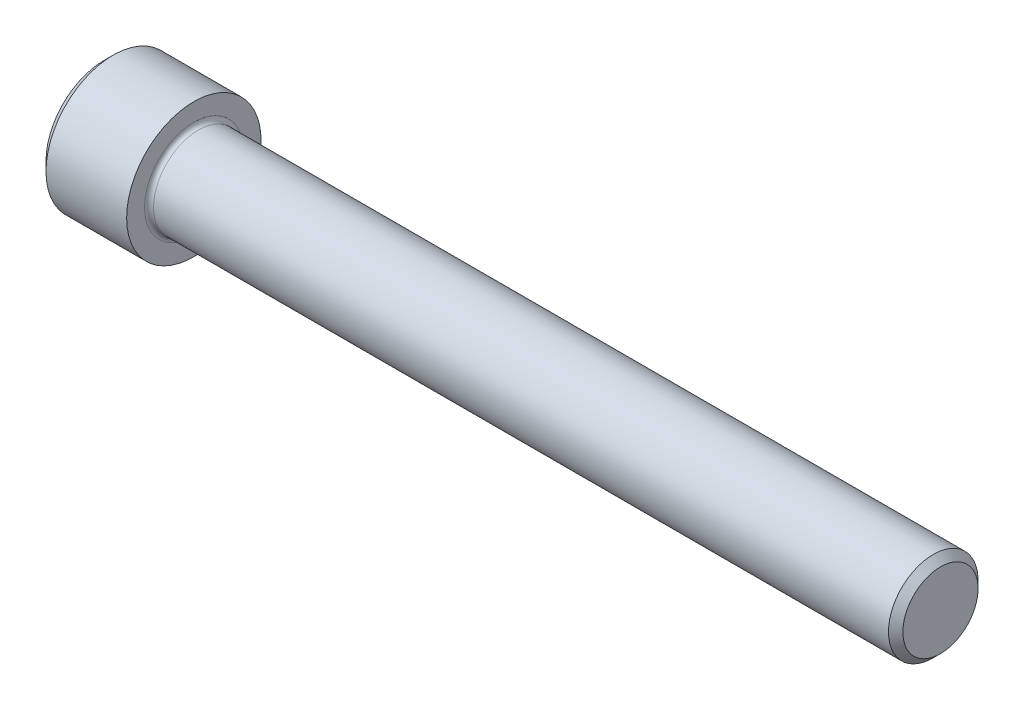
SolidWorks part; units mm, degrees
ref_plane "Plane1" through (0, 0, 0) normal (0, 0, 1) x (1, 0, 0)
ref_plane "Plane2" through (0, 0, 0) normal (0, 1, 0) x (1, 0, 0)
ref_plane "Plane3" through (0, 0, 0) normal (1, 0, 0) x (0, 0, -1)
sketch "BodySke" plane through (0, 0, 0) normal (0, 0, 1) x (1, 0, 0)
  line L0 (0, 0) -> (0, 7.8)
  line L1 (1.2, 9) -> (12, 9)
  line L2 (12, 9) -> (12, 6)
  line L3 (12, 6) -> (111.036, 6)
  line L4 (112, 5.036) -> (112, 0)
  line L5 (112, 0) -> (0, 0)
  line L6 (-31.75, 0) -> (127, 0) construction
  line L7 (0, 7.8) -> (1.2, 9)
  line L8 (112, 5.036) -> (111.036, 6)
  line L9 (0, -7.8) -> (1.2, -9) construction
  line L10 (112, -5.036) -> (111.036, -6) construction
  line L11 (13.75, 9.525) -> (13.75, 3.175) construction
  line L12 (76, 9.525) -> (76, 3.175) construction
  line L13 (62, 9.525) -> (62, 3.175) construction
  dimension "Diameter" = 12
  dimension "Head_ht" = 12
  dimension "Length" = 100
  dimension "Body_ch_ang" = 45
  dimension "Head_dia" = 18
  dimension "Head_ch_ang" = 45
  dimension "Minor_dia" = 10.072
  dimension "Advance" = 1.75
  dimension "Thread_nom" = 36
  dimension "Thread_length" = 50
  dimension "Head_ch_ht" = 1.2
revolve "Base-Revolve" add sketch "BodySke"
cosmetic thread "ThreadCosmetic" [suppressed]
fillet "Fillet1" radius 0.6 1 edges at (12, 0, 6)
sketch "Sketch2" plane through (0, 0, 0) normal (0, 0, 1) x (1, 0, 0)
  line L0 (0, 5.0575) -> (6, 5.0575)
  line L1 (6, 5.0575) -> (8.9199, 0)
  line L2 (-31.75, 0) -> (127, 0) construction
  line L3 (8.9199, 0) -> (0, 0)
  line L4 (0, 0) -> (0, 5.0575)
  line L5 (0, 7.8) -> (0, -7.8) construction
  line L6 (0, 0) -> (47.625, 0) construction
  line L7 (12, -9) -> (12, 9) construction
  dimension "D1" = 5.0575
  dimension "D2" = 60
  dimension "Wall_thickness" = 6
revolve "Hex-PreBroach" cut sketch "Sketch2" angle 360 about L6
sketch "Sketch3" plane through (0, 0, 0) normal (-1, 0, 0) x (0, 0.5, 0.866)
  line L0 (2.9199, 5.0575) -> (-2.9199, 5.0575)
  line L1 (-2.9199, 5.0575) -> (-5.8399, 0)
  line L2 (2.9199, 5.0575) -> (5.8399, 0)
  line L3 (2.9199, -5.0575) -> (5.8399, 0)
  line L4 (2.9199, -5.0575) -> (-2.9199, -5.0575)
  line L5 (-2.9199, -5.0575) -> (-5.8399, 0)
  dimension "D1" = 5.0575
  dimension "D2" = 5.0575
  dimension "Hex_size" = 10.115
extrude "Hex" cut sketch "Sketch3" against normal blind 6
sketch "Sketch4" plane through (0, 0, 0) normal (-1, 0, 0) x (0, 0, 1)
  line L0 (0, 0) -> (3.7846, 0)
  line L1 (0, 0) -> (6.1484, 3.5498) construction
  line L2 (0, 0) -> (1.8923, 3.2776)
  line L3 (3.1235, 0.8061) -> (3.6229, 1.0945)
  line L4 (2.2599, 2.3019) -> (2.7593, 2.5903)
  arc A0 (3.1235, 0.8061) -> (2.2599, 2.3019) centre (0, 0) ccw
  arc A1 (3.7846, 0) -> (3.6229, 1.0945) centre (0, 0) ccw
  arc A2 (1.8923, 3.2776) -> (2.7593, 2.5903) centre (0, 0) cw
  dimension "D1" = 30
  dimension "Spline_n_dim" = 6.4516
  dimension "Spline_m_dim" = 7.5692
  dimension "D2" = 60
  dimension "D3" = 0.8636
  dimension "Spline_p_dim" = 1.7272
extrude "Spline" [suppressed] cut sketch "Sketch4" against normal blind 6
pattern_circular "CirPattern1" [suppressed] count 6 every 60
sketch "Sketch5" plane through (0, 0, 0) normal (0, 0, 1) x (1, 0, 0)
  line L0 (-31.75, 0) -> (127, 0) construction
  line L2 (0, 7.8) -> (0, -7.8) construction
  circle A0 centre (4, 0) radius 0.825
  dimension "Drilled_hole_dia" = 1.65
  dimension "Drilled_hole_loc" = 4
extrude "Hole" [suppressed] cut sketch "Sketch5" against normal through all and the other way through all
pattern_circular "Drilled-4" [suppressed] count 2 every 60
pattern_circular "Drilled-6" [suppressed] count 3 every 60
sketch "ThdSchSke" plane through (0, 0, 0) normal (0, 0, 1) x (1, 0, 0)
  line L0 (76, -5.036) -> (75.325, -6)
  line L1 (76, -5.036) -> (76.675, -6)
  line L2 (76.675, -6) -> (76.675, -7.5)
  line L3 (-3.175, 0) -> (5.1513, 0) construction
  line L5 (76.675, -7.5) -> (75.325, -7.5)
  line L6 (75.325, -7.5) -> (75.325, -6)
  line L7 (0, 7.8) -> (0, -7.8) construction
  dimension "Thread_minor" = 10.072
  dimension "Diameter" = 12
  dimension "Start" = 76
  dimension "SideAngle" = 55
  dimension "VeeAngle" = 70
  dimension "Overcut" = 15
revolve "ThreadSchematic" [suppressed] cut sketch "ThdSchSke" angle 360 about L3
pattern_linear "ThdSchPat" [suppressed]
equation "\"D2@Sketch3\" = \"Hex_size@Sketch3\" / 2"
equation "\"D1@Sketch3\" = \"Hex_size@Sketch3\" / 2"
equation "\"D1@Sketch2\" = \"Hex_size@Sketch3\" / 2"
equation "\"D3@Sketch4\" = \"Spline_p_dim@Sketch4\" / 2"
equation "\"Thread_minor@ThreadCosmetic\"  =  \"Minor_dia@BodySke\""
equation "\"D2@CirPattern1\" = 360 / \"Num_teeth@CirPattern1\""
equation "\"Wall_thickness@Sketch2\" = \"Head_ht@BodySke\" - \"Key_eng@Hex\""
equation "\"Thread_length@ThreadCosmetic\" = ((sgn( (\"Length@BodySke\" - \"Advance@BodySke\" ) - \"Thread_nom@BodySke\" )-1)*( (\"Length@BodySke\" - \"Advance@BodySke\" ) - \"Thread_nom@BodySke\" ))/-2+ \"Thread_nom@BodySke\""
equation "\"Thread_minor@ThdSchSke\" = \"Minor_dia@BodySke\""
equation "\"Diameter@ThdSchSke\" = \"Diameter@BodySke\""
equation "\"Overcut@ThdSchSke\" = \"Diameter@BodySke\" * 1.25"
equation "\"Start@ThdSchSke\" = \"Head_ht@BodySke\" + \"Length@BodySke\" - \"Thread_length@ThreadCosmetic\"  '---Non-countersunk---"
equation "\"Num_threads@ThdSchPat\" = int( \"Thread_length@ThreadCosmetic\" / \"Advance@BodySke\" + 0.999 )  + 1"
equation "\"Advance@ThdSchPat\" = \"Thread_length@ThreadCosmetic\" /  (\"Num_threads@ThdSchPat\" - 1) 'relax it"
equation "\"Num_threads@ThdSchPat\" = \"Num_threads@ThdSchPat\" - sgn( \"Num_threads@ThdSchPat\" - 1) '---chamfered tips only---"
